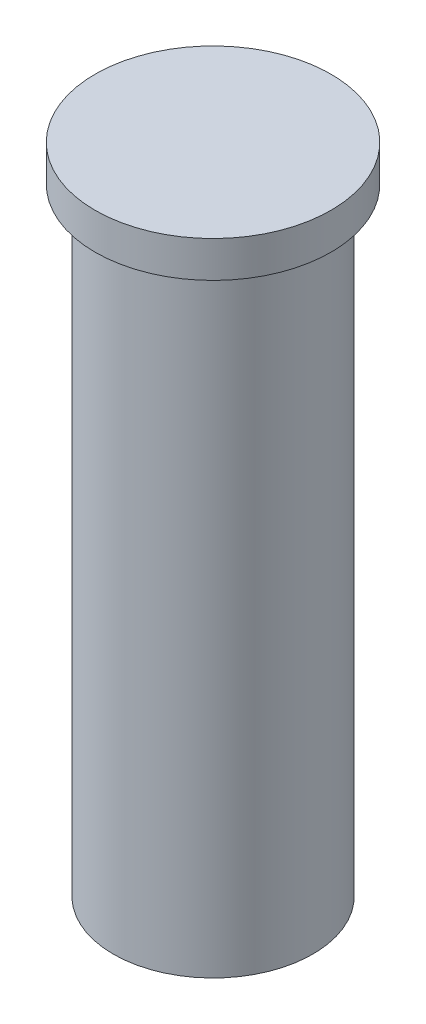
SolidWorks part; units mm, degrees
material "PVC Rigid"
ref_plane "Front Plane" through (0, 0, 0) normal (0, 0, 1) x (1, 0, 0)
ref_plane "Top Plane" through (0, 0, 0) normal (0, 1, 0) x (1, 0, 0)
ref_plane "Right Plane" through (0, 0, 0) normal (1, 0, 0) x (0, 0, -1)
sketch "Sketch1" plane through (0, 0, 0) normal (0, 1, 0) x (1, 0, 0)
  circle A0 centre (0, 0) radius 22.5
  circle A1 centre (0, 0) radius 27.5
  dimension "D1" = 45
  dimension "D2" = 5
extrude "Boss-Extrude1" add sketch "Sketch1" along normal blind 170
sketch "Sketch2" plane through (0, 170, 0) normal (0, 1, 0) x (1, 0, 0)
  circle A0 centre (0, 0) radius 32.5
  dimension "D1" = 65
extrude "Boss-Extrude2" add sketch "Sketch2" along normal blind 10
